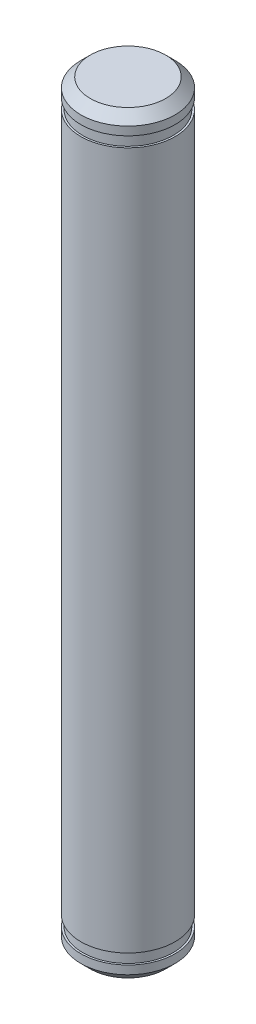
SolidWorks part; units mm, degrees
ref_plane "前视基准面" through (0, 0, 0) normal (0, 0, 1) x (1, 0, 0)
ref_plane "上视基准面" through (0, 0, 0) normal (0, 1, 0) x (1, 0, 0)
ref_plane "右视基准面" through (0, 0, 0) normal (1, 0, 0) x (0, 0, -1)
other "Configuration Table"
sketch "草图1" plane through (0, 0, 0) normal (0, 0, 1) x (1, 0, 0)
  line L0 (0, 17.9143) -> (0, -10.0949) construction
  line L1 (0, 40) -> (5, 40)
  line L2 (5, 40) -> (5, 30)
  line L4 (5, 30) -> (5, -30)
  line L6 (5, -30) -> (5, -40)
  line L7 (5, -40) -> (0, -40)
  line L8 (0, 0) -> (25.4592, 0) construction
  line L9 (0, 40) -> (0, -40)
  dimension "D1" = 5
  dimension "D3" = 60
  dimension "D4" = 10
  dimension "D5" = 10
revolve "旋转1" add sketch "草图1" angle 360 about L9
chamfer "倒角1" distance 1 angle 45 2 edges at (-5, -40, 0) (-5, 40, 0)
ref_plane "基准面1" through (0, 0, 0) normal (0, 1, 0) x (1, 0, 0)
sketch "草图2" plane through (0, 40, 0) normal (0, 1, 0) x (1, 0, 0)
  circle A0 centre (0, 0) radius 5 construction
  circle A1 centre (0, 0) radius 5
  circle A2 centre (0, 0) radius 4.8
  dimension "D1" = 9.6
extrude "切除-拉伸1" cut sketch "草图2" along normal blind 1.1 from offset 3 offset against normal yes
mirror "镜向1" about plane through (0, 0, 0) normal (0, 1, 0) of "切除-拉伸1"
